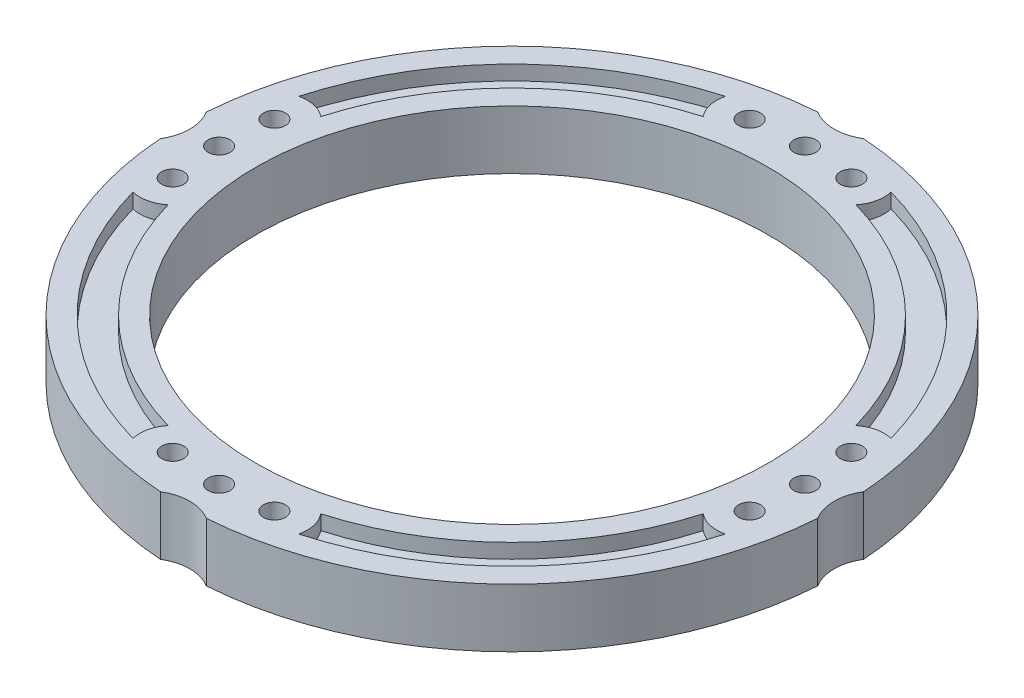
SolidWorks part; units mm, degrees
ref_plane "Front Plane" through (0, 0, 0) normal (0, 0, 1) x (1, 0, 0)
ref_plane "Top Plane" through (0, 0, 0) normal (0, 1, 0) x (1, 0, 0)
ref_plane "Right Plane" through (0, 0, 0) normal (1, 0, 0) x (0, 0, -1)
sketch "Sketch1" plane through (0, 0, 0) normal (0, 1, 0) x (1, 0, 0)
  line L0 (0, 40) -> (0, 0) construction
  line L1 (0, 0) -> (-6.9459, 39.3923) construction
  line L2 (0, 0) -> (6.9459, 39.3923) construction
  circle A0 centre (0, 0) radius 40 construction
  circle A1 centre (0, 40) radius 1.5
  circle A2 centre (40, 0) radius 1.5
  circle A3 centre (0, -40) radius 1.5
  circle A4 centre (-40, 0) radius 1.5
  circle A5 centre (0, 0) radius 35
  circle A6 centre (0, 0) radius 45
  circle A7 centre (6.9459, 39.3923) radius 1.5
  circle A8 centre (-6.9459, 39.3923) radius 1.5
  circle A9 centre (39.3923, 6.9459) radius 1.5
  circle A10 centre (39.3923, -6.9459) radius 1.5
  circle A11 centre (6.9459, -39.3923) radius 1.5
  circle A12 centre (-6.9459, -39.3923) radius 1.5
  circle A13 centre (-39.3923, -6.9459) radius 1.5
  circle A14 centre (-39.3923, 6.9459) radius 1.5
  point P14 (0, 0)
  point P33 (0, 0)
  dimension "D1" = 80
  dimension "D2" = 3
  dimension "D4" = 5
  dimension "D5" = 5
  dimension "D6" = 3
  dimension "D7" = 3
  dimension "D8" = 10
  dimension "D9" = 10
  dimension "D3" = 4
  dimension "D10" = 4
extrude "Boss-Extrude1" add sketch "Sketch1" along normal blind 8
sketch "Sketch2" plane through (0, 8, 0) normal (0, 1, 0) x (1, 0, 0)
  circle A5 centre (0, 0) radius 38
  circle A6 centre (0, 0) radius 38
  circle A8 centre (0, 0) radius 42
  circle A9 centre (0, 0) radius 42
  circle A14 centre (-6.9459, 39.3923) radius 4.5
  circle A15 centre (-6.9459, 39.3923) radius 4.5
  circle A16 centre (39.3923, 6.9459) radius 4.5
  circle A17 centre (6.9459, 39.3923) radius 4.5
  circle A18 centre (6.9459, 39.3923) radius 4.5
  circle A19 centre (39.3923, -6.9459) radius 4.5
  circle A20 centre (6.9459, -39.3923) radius 4.5
  circle A21 centre (-6.9459, -39.3923) radius 4.5
  circle A22 centre (-39.3923, -6.9459) radius 4.5
  circle A23 centre (-39.3923, 6.9459) radius 4.5
  point P27 (0, 0)
  dimension "D1" = 3
  dimension "D2" = 3
  dimension "D3" = 3
  dimension "D4" = 3
  dimension "D5" = 4
extrude "Cut-Extrude1" cut sketch "Sketch2" against normal blind 2 contours A23 A6 A15 A9 | A18 A6 A16 A9 | A20 A9 A19 A6 | A22 A9 A21 A6
sketch "Sketch3" plane through (0, 0, 0) normal (0, -1, 0) x (1, 0, 0)
  circle A2 centre (0, 0) radius 38
  circle A3 centre (0, 0) radius 38
  circle A5 centre (0, 0) radius 42
  circle A6 centre (0, 0) radius 42
  circle A8 centre (-6.9459, 39.3923) radius 4.5
  circle A9 centre (-6.9459, 39.3923) radius 4.5
  circle A10 centre (39.3923, -6.9459) radius 4.5
  circle A11 centre (6.9459, 39.3923) radius 4.5
  circle A12 centre (6.9459, 39.3923) radius 4.5
  circle A13 centre (39.3923, 6.9459) radius 4.5
  circle A14 centre (-6.9459, -39.3923) radius 4.5
  circle A15 centre (6.9459, -39.3923) radius 4.5
  circle A16 centre (-39.3923, 6.9459) radius 4.5
  circle A17 centre (-39.3923, -6.9459) radius 4.5
  point P27 (0, 0)
  dimension "D1" = 3
  dimension "D2" = 3
  dimension "D3" = 3
  dimension "D4" = 3
  dimension "D5" = 4
extrude "Cut-Extrude2" cut sketch "Sketch3" against normal blind 2 contours A15 A6 A10 A3 | A17 A6 A14 A3 | A16 A3 A9 A6 | A13 A6 A12 A3
sketch "Sketch4" plane through (0, 0, 0) normal (0, -1, 0) x (-1, 0, 0)
  circle A0 centre (0, 0) radius 50
  circle A1 centre (0, 50) radius 6
  circle A2 centre (50, 0) radius 6
  circle A3 centre (0, -50) radius 6
  circle A4 centre (-50, 0) radius 6
  point P14 (0, 0)
  circle M11 centre (0, 0) radius 45
  dimension "D1" = 100
  dimension "D2" = 12
  dimension "D3" = 4
extrude "Cut-Extrude3" cut sketch "Sketch4" against normal blind 10 contours A2 M11 | A3 M11 | A4 M11 | A1 M11
